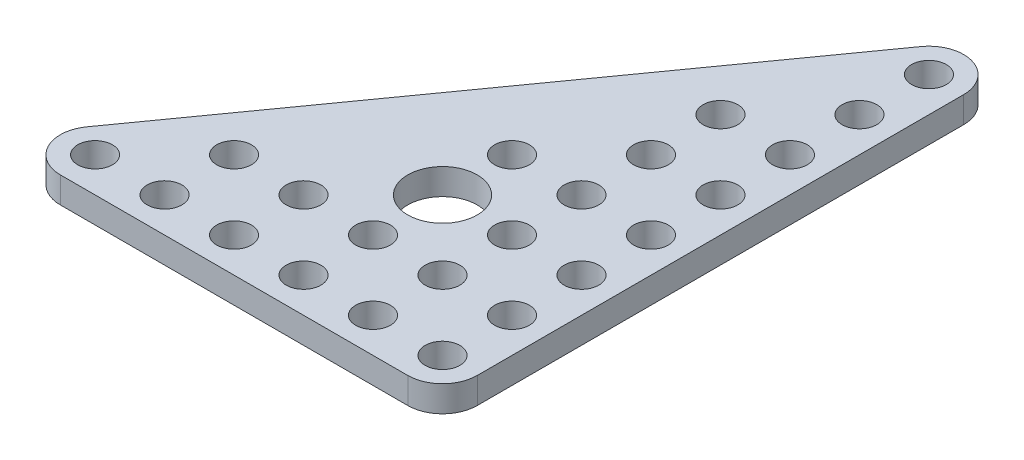
SolidWorks part; units mm, degrees
material "6061 Alloy"
ref_plane "前视基准面" through (0, 0, 0) normal (0, 0, 1) x (1, 0, 0)
ref_plane "上视基准面" through (0, 0, 0) normal (0, 1, 0) x (1, 0, 0)
ref_plane "右视基准面" through (0, 0, 0) normal (1, 0, 0) x (0, 0, -1)
other "Configuration Table"
sketch "Sketch2" plane through (0, 0, 0) normal (0, 1, 0) x (1, 0, 0)
  line L0 (17.1804, -22.9288) -> (17.1804, 33.0712)
  line L1 (9.9254, 35.3961) -> (-30.0746, -20.6039)
  line L2 (-26.8196, -26.9288) -> (13.1804, -26.9288)
  arc A0 (17.1804, 33.0712) -> (9.9254, 35.3961) centre (13.1804, 33.0712) ccw
  arc A1 (-30.0746, -20.6039) -> (-26.8196, -26.9288) centre (-26.8196, -22.9288) ccw
  arc A2 (17.1804, -22.9288) -> (13.1804, -26.9288) centre (13.1804, -22.9288) cw
  dimension "D1" = 4
  dimension "D2" = 4
  dimension "D3" = 4
  dimension "D4" = 56
  dimension "D5" = 40
sketch "Sketch4" plane through (0, 0, 0) normal (0, 1, 0) x (1, 0, 0)
  circle A0 centre (13.1804, -22.9288) radius 2
  circle A1 centre (13.1804, -14.9288) radius 2
  circle A2 centre (13.1804, -6.9288) radius 2
  circle A3 centre (13.1804, 1.0712) radius 2
  circle A4 centre (13.1804, 9.0712) radius 2
  circle A5 centre (13.1804, 17.0712) radius 2
  circle A6 centre (13.1804, 25.0712) radius 2
  circle A7 centre (13.1804, 33.0712) radius 2
  circle A8 centre (5.1804, -22.9288) radius 2
  circle A9 centre (-2.8196, -22.9288) radius 2
  circle A10 centre (-10.8196, -22.9288) radius 2
  circle A11 centre (-18.8196, -22.9288) radius 2
  circle A12 centre (-26.8196, -22.9288) radius 2
  circle A13 centre (-18.8196, -14.9288) radius 2
  circle A14 centre (-10.8196, -14.9288) radius 2
  circle A15 centre (-2.8196, -14.9288) radius 2
  circle A16 centre (5.1804, -14.9288) radius 2
  circle A17 centre (5.1804, -6.9288) radius 2
  circle A18 centre (5.1804, 1.0712) radius 2
  circle A19 centre (5.1804, 9.0712) radius 2
  circle A20 centre (5.1804, 17.0712) radius 2
  circle A22 centre (-2.8196, 1.0712) radius 2
  circle A23 centre (-2.8196, -6.9288) radius 4
  dimension "D1" = 8
  dimension "D4" = 8
  dimension "D7" = 8
  dimension "D2" = 8
  dimension "D3" = 8
  dimension "D5" = 8
  dimension "D6" = 8
  dimension "D8" = 8
  dimension "D9" = 8
  dimension "D10" = 8
extrude "Boss-Extrude2" add sketch "Sketch2" along normal blind 3 contours L1 A1 L2 A2 L0 A0
extrude "Cut-Extrude3" cut sketch "Sketch4" along normal blind 7
